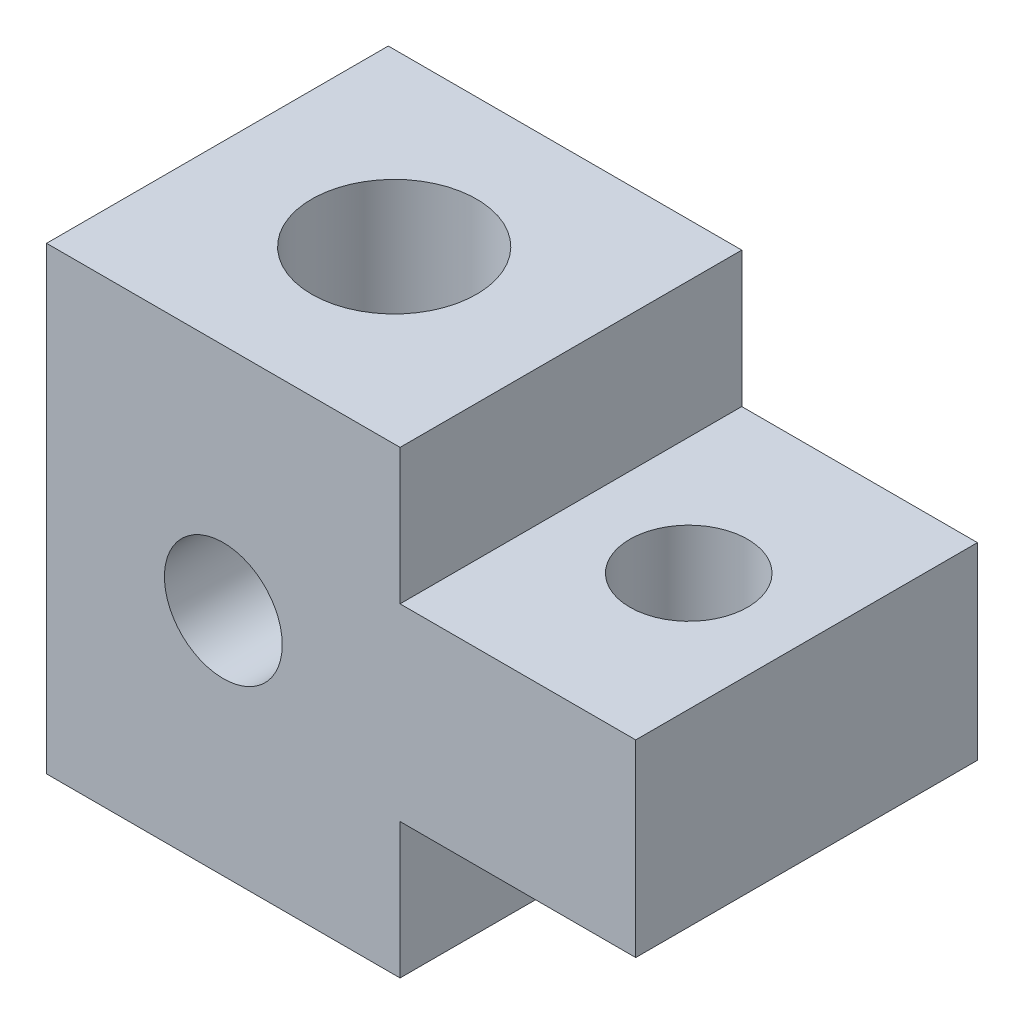
SolidWorks part; units mm, degrees
ref_plane "Plan de face" through (0, 0, 0) normal (0, 0, 1) x (1, 0, 0)
ref_plane "Plan de dessus" through (0, 0, 0) normal (0, 1, 0) x (1, 0, 0)
ref_plane "Plan de droite" through (0, 0, 0) normal (1, 0, 0) x (0, 0, -1)
sketch "Esquisse1" plane through (0, 0, 0) normal (0, 0, 1) x (1, 0, 0)
  line L0 (0, 0) -> (107.8789, 0) construction
  line L1 (30, -8) -> (50, -8)
  line L2 (0, 0) -> (30, 0)
  line L3 (0, -19.5) -> (0, 19.5)
  line L4 (0, 19.5) -> (30, 19.5)
  line L5 (30, -19.5) -> (30, 19.5)
  line L6 (30, 0) -> (50, 0)
  line L7 (30, -8) -> (30, 8)
  line L8 (30, 8) -> (50, 8)
  line L9 (50, -8) -> (50, 8)
  line L10 (0, -19.5) -> (30, -19.5)
  dimension "D1" = 50
  dimension "D2" = 30
  dimension "D3" = 16
  dimension "D4" = 39
extrude "Boss.-Extru.1" add sketch "Esquisse1" along normal blind 29 contours L2 L5 L4 L3 | L3 L10 L5 L2 | L1 L9 L6 L5 | L6 L9 L8 L5
sketch "Esquisse2" plane through (0, 19.5, 0) normal (0, 1, 0) x (1, 0, 0)
  line L0 (30, 0) -> (50, 0) construction
  line L1 (0, 0) -> (30, 0) construction
  line L2 (50, -29) -> (50, 0) construction
  line L3 (30, -29) -> (30, 0) construction
  circle A0 centre (15, -14.5) radius 7
  circle A1 centre (40, -14.5) radius 5
  point P7 (40, 0)
  point P10 (15, 0)
  point P13 (50, -14.5)
  point P17 (30, -14.5)
  dimension "D1" = 10
  dimension "D2" = 14
extrude "Enlèv. mat.-Extru.1" cut sketch "Esquisse2" against normal through all
sketch "Esquisse4" plane through (0, 0, 29) normal (0, 0, 1) x (1, 0, 0)
  line L0 (0, 19.5) -> (30, 19.5) construction
  circle A0 centre (15, 0) radius 5
  point P2 (0, 0)
  point P4 (0, 0)
  point P7 (15, 19.5)
  dimension "D1" = 10
extrude "Enlèv. mat.-Extru.2" cut sketch "Esquisse4" against normal through all
